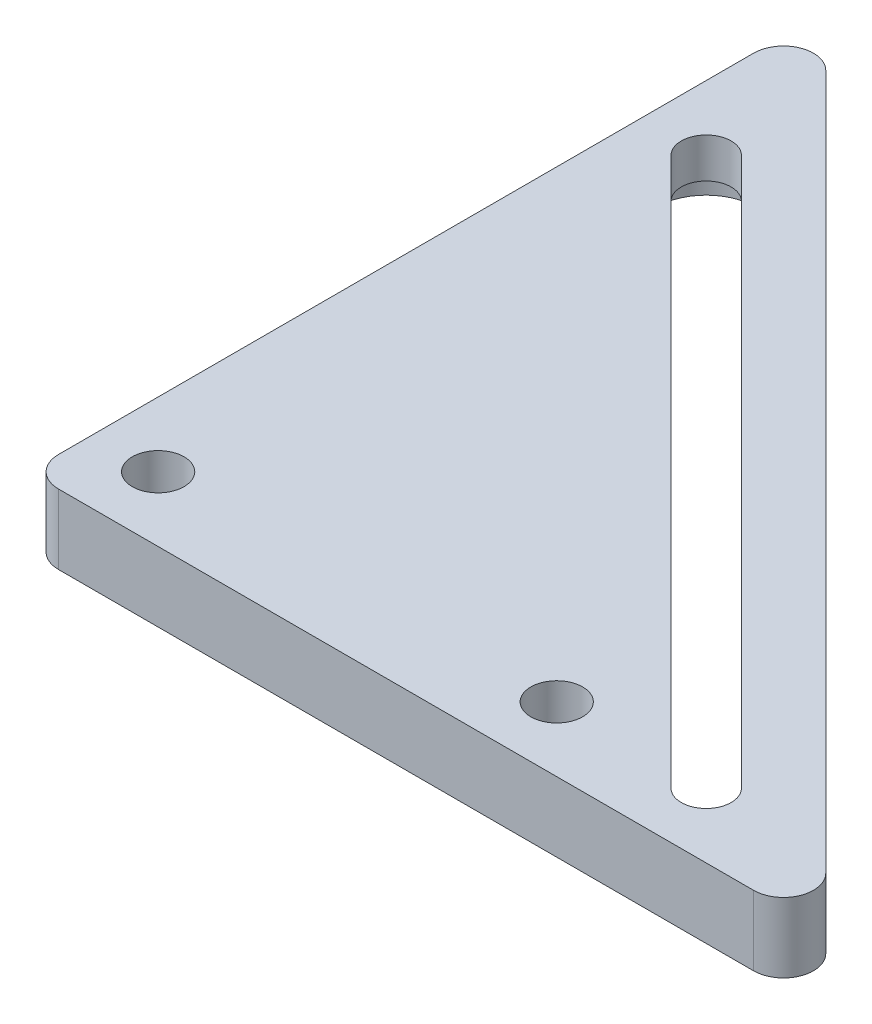
SolidWorks part; units mm, degrees
ref_plane "前视基准面" through (0, 0, 0) normal (0, 0, 1) x (1, 0, 0)
ref_plane "上视基准面" through (0, 0, 0) normal (0, 1, 0) x (1, 0, 0)
ref_plane "右视基准面" through (0, 0, 0) normal (1, 0, 0) x (0, 0, -1)
other "Configuration Table"
sketch "草图1" plane through (0, 0, 0) normal (0, 1, 0) x (1, 0, 0)
  line L0 (0, 0) -> (0, 80)
  line L1 (0, 0) -> (80, 0)
  line L2 (0, 80) -> (80, 0)
  dimension "D1" = 80
  dimension "D2" = 80
extrude "凸台-拉伸1" add sketch "草图1" along normal blind 10
sketch "草图2" plane through (0, 0, 0) normal (0, -1, 0) x (1, 0, 0)
  line L0 (6.5, -61.5) -> (61.5, -6.5)
  line L1 (2.9645, -57.9645) -> (57.9645, -2.9645)
  line L2 (10.0355, -65.0355) -> (65.0355, -10.0355)
  line L3 (80, 0) -> (0, -80)
  line L4 (0, 0) -> (80, 0)
  line L5 (0, -6.5) -> (80, -6.5)
  line L6 (0, 0) -> (0, -80)
  line L7 (6.5, 0) -> (6.5, -80)
  circle A0 centre (6.5, -6.5) radius 3
  circle A1 centre (61.5, -6.5) radius 5
  circle A2 centre (6.5, -61.5) radius 5
  dimension "D3" = 6
  dimension "D4" = 10
  dimension "D6" = 10
  dimension "D5" = 55
  dimension "D7" = 55
  dimension "D1" = 6.5
  dimension "D2" = 6.5
sketch "草图5" plane through (0, 10, 0) normal (0, 1, 0) x (1, 0, 0)
  line L0 (6.5, 0) -> (6.5, 80) construction
  line L1 (0, 6.5) -> (80, 6.5) construction
  circle A0 centre (6.5, 6.5) radius 2.6
  circle A1 centre (6.5, 46.5) radius 2.6
  circle A2 centre (46.5, 6.5) radius 2.6
  dimension "D2" = 5.2
  dimension "D3" = 5.2
  dimension "D4" = 5.2
  dimension "D1" = 40
  dimension "D5" = 40
extrude "切除-拉伸3" cut sketch "草图5" against normal blind 10
fillet "圆角5" radius 3 1 edges at (80, 5, 0)
fillet "圆角6" radius 3 1 edges at (0, 5, -80)
fillet "圆角7" radius 3 1 edges at (0, 5, 0)
sketch "草图7" plane through (0, 10, 0) normal (0, 1, 0) x (1, 0, 0)
  circle A0 centre (6.5, 6.5) radius 5.5
  circle A1 centre (6.5, 46.5) radius 5.5
  circle A2 centre (46.5, 6.5) radius 5.5
  dimension "D1" = 11
  dimension "D2" = 11
  dimension "D3" = 11
extrude "切除-拉伸4" cut sketch "草图7" against normal blind 5
sketch "草图10" plane through (0, 10, 0) normal (0, 1, 0) x (1, 0, 0)
  line L1 (-89.9322, -86.5453) -> (80.7675, -86.5453)
  line L2 (-89.9322, -86.5453) -> (-89.9322, 80.4467)
  line L3 (-89.9322, 80.4467) -> (80.7675, 80.4467)
  line L4 (80.7675, -86.5453) -> (80.7675, 80.4467)
  line L5 (-89.9322, -86.5453) -> (80.7675, 80.4467) construction
  line L6 (-89.9322, 80.4467) -> (80.7675, -86.5453) construction
  point P0 (-4.5824, -3.0493)
sketch "草图12" plane through (0, 0, 0) normal (0, -1, 0) x (1, 0, 0)
  line L0 (-993.5, -46.5) -> (49006.5, -46.5) construction
  circle A0 centre (8.5, -46.5) radius 2.5537
  circle A1 centre (6.5, -46.5) radius 2.6 construction
  dimension "D1" = 2
extrude "切除-拉伸9" cut sketch "草图12" against normal blind 9
sketch "草图13" plane through (0, 0, 0) normal (0, -1, 0) x (1, 0, 0)
  circle A0 centre (6.5, -46.5) radius 2.6
  circle A1 centre (8.5, -46.5) radius 2.5537
  arc M6 (7.5597, -48.8743) -> (7.5597, -44.1257) centre (6.5, -46.5) cw
extrude "凸台-拉伸2" add sketch "草图13" against normal blind 5 contours A1 M6
sketch "草图14" plane through (0, 5, 0) normal (0, 1, 0) x (1, 0, 0)
  circle A0 centre (6.5, 46.5) radius 5.5
  circle A1 centre (8.5, 46.5) radius 5.5
  circle M3 centre (6.5, 46.5) radius 5.5
  dimension "D1" = 11
extrude "切除-拉伸12" cut sketch "草图14" along normal blind 5 contours A1 M3
sketch "草图21" plane through (0, 5, 0) normal (0, 1, 0) x (1, 0, 0)
  circle A0 centre (8.5, 46.5) radius 5.5
  circle A1 centre (6.5, 46.5) radius 5.5
  arc M2 (7.5, 51.9083) -> (7.5, 41.0917) centre (6.5, 46.5) ccw
extrude "凸台-拉伸6" add sketch "草图21" along normal blind 5 contours A0 M2
sketch "草图22" plane through (0, 5, 0) normal (0, 1, 0) x (1, 0, 0)
  circle A0 centre (8.5, 46.5) radius 5.5
extrude "凸台-拉伸7" add sketch "草图22" along normal blind 5
sketch "草图24" plane through (0, 10, 0) normal (0, 1, 0) x (1, 0, 0)
  circle A0 centre (8.5, 46.5) radius 5.5
extrude "切除-拉伸14" cut sketch "草图24" against normal blind 3
sketch "草图25" plane through (0, 5, 0) normal (0, -1, 0) x (1, 0, 0)
  circle A0 centre (8.5, -46.5) radius 2.65
  dimension "D1" = 5.3
extrude "切除-拉伸15" cut sketch "草图25" against normal blind 3
sketch "草图26" plane through (0, 0, 0) normal (0, -1, 0) x (1, 0, 0)
  circle A0 centre (8.5, -46.5) radius 2.65
  dimension "D1" = 5.3
extrude "切除-拉伸16" cut sketch "草图26" against normal blind 5
sketch "草图29" plane through (0, 0, 0) normal (0, -1, 0) x (1, 0, 0)
  circle A0 centre (8.5, -46.5) radius 2.65
extrude "凸台-拉伸8" add sketch "草图29" against normal blind 10
sketch "草图30" plane through (0, 7, 0) normal (0, 1, 0) x (1, 0, 0)
  circle A0 centre (8.5, 46.5) radius 5.5
extrude "凸台-拉伸9" add sketch "草图30" along normal blind 3
extrude "切除-拉伸18" cut sketch "草图2" against normal blind 3 contours A2 L0 A1 L5 L1 L7 | A2 L2 A1 L0 | L7 A2 | L7 A2 L0 | L0 A2 L7 | A2 L7 L1 | A1 L1 L5 | L5 A1 | L5 A1 L0 | A1 L5 L0
sketch "草图33" plane through (0, 10, 0) normal (0, 1, 0) x (1, 0, 0)
  circle A0 centre (6.5, 6.5) radius 5.5
  circle A1 centre (6.5, 6.5) radius 2.6
  circle A2 centre (46.5, 6.5) radius 2.6
  circle A3 centre (46.5, 6.5) radius 5.5
extrude "凸台-拉伸10" add sketch "草图33" against normal blind 5
sketch "草图34" plane through (0, 10, 0) normal (0, 1, 0) x (1, 0, 0)
  line L1 (-21.8892, 87.5282) -> (96.7667, 87.5282)
  line L2 (-21.8892, 87.5282) -> (-21.8892, -20.9465)
  line L3 (-21.8892, -20.9465) -> (96.7667, -20.9465)
  line L4 (96.7667, 87.5282) -> (96.7667, -20.9465)
extrude "切除-拉伸20" cut sketch "草图34" against normal blind 3
sketch "草图35" plane through (0, 3, 0) normal (0, -1, 0) x (1, 0, 0)
  line L4 (8.2678, -63.2678) -> (63.2678, -8.2678)
  line L5 (59.7322, -4.7322) -> (4.7322, -59.7322)
  line L6 (8.2678, -63.2678) -> (63.2678, -8.2678)
  line L7 (59.7322, -4.7322) -> (4.7322, -59.7322)
  arc A4 (63.2678, -8.2678) -> (59.7322, -4.7322) centre (61.5, -6.5) ccw
  arc A5 (4.7322, -59.7322) -> (8.2678, -63.2678) centre (6.5, -61.5) ccw
  arc A6 (63.2678, -8.2678) -> (59.7322, -4.7322) centre (61.5, -6.5) ccw
  arc A7 (4.7322, -59.7322) -> (8.2678, -63.2678) centre (6.5, -61.5) ccw
  dimension "D1" = 2.5
extrude "切除-拉伸21" cut sketch "草图35" against normal through all
